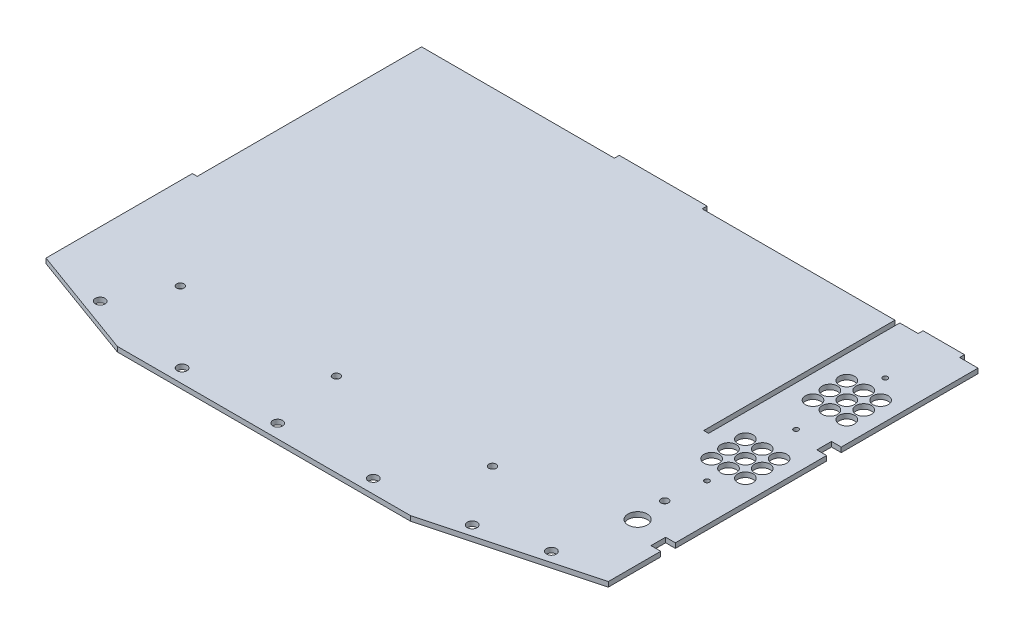
SolidWorks part; units mm, degrees
material "6061-T6 (SS)"
ref_plane "X-Y Datum" through (0, 0, 0) normal (0, 0, 1) x (1, 0, 0)
ref_plane "X-Z Datum" through (0, 0, 0) normal (0, 1, 0) x (1, 0, 0)
ref_plane "Y-Z Datum" through (0, 0, 0) normal (1, 0, 0) x (0, 0, -1)
sketch "Sketch1" plane through (0, 0, 0) normal (0, 0, 1) x (1, 0, 0)
  line L1 (-154.0408, -1.5875) -> (154.0408, -1.5875)
  line L2 (-154.0408, -1.5875) -> (-154.0408, 1.5875)
  line L3 (-154.0408, 1.5875) -> (154.0408, 1.5875)
  line L4 (154.0408, -1.5875) -> (154.0408, 1.5875)
  line L5 (-154.0408, -1.5875) -> (154.0408, 1.5875) construction
  line L6 (-154.0408, 1.5875) -> (154.0408, -1.5875) construction
  point P0 (0, 0)
  dimension "D1" = 3.175
  dimension "D2" = 308.0817
extrude "Boss-Extrude1" add sketch "Sketch1" along normal blind 267.83
sketch "Sketch3" plane through (154.0408, 0, 0) normal (1, 0, 0) x (0, 0, -1)
  line L9 (0, -1.5875) -> (0, 1.5875)
  line L10 (0, 1.5875) -> (-267.83, 1.5875)
  line L11 (-267.83, 1.5875) -> (-267.83, -1.5875)
  line L12 (-267.83, -1.5875) -> (0, -1.5875)
  line L13 (0, -1.5875) -> (0, 1.5875)
  line L14 (0, 1.5875) -> (-267.83, 1.5875)
  line L15 (-267.83, 1.5875) -> (-267.83, -1.5875)
  line L16 (-267.83, -1.5875) -> (0, -1.5875)
  dimension "D1" = 0
extrude "Boss-Extrude3" add sketch "Sketch3" along normal blind 3.175
sketch "Sketch4" plane through (0, 0, 267.83) normal (0, 0, 1) x (1, 0, 0)
  line L1 (157.2158, -1.5875) -> (208.1047, -1.5875)
  line L2 (157.2158, -1.5875) -> (157.2158, 1.5875)
  line L3 (157.2158, 1.5875) -> (208.1047, 1.5875)
  line L4 (208.1047, -1.5875) -> (208.1047, 1.5875)
  dimension "D1" = 3.175
  dimension "D2" = 50.8889
extrude "Boss-Extrude4" add sketch "Sketch4" against normal blind 267.83
sketch "Sketch6" plane through (0, 1.5875, 0) normal (0, 1, 0) x (1, 0, 0)
  line L0 (106.5047, -267.83) -> (106.5047, -223.38)
  line L1 (208.1047, -267.83) -> (-154.0408, -267.83) construction
  line L2 (208.1047, -223.38) -> (106.5047, -223.38)
  line L3 (208.1047, 0) -> (208.1047, -267.83) construction
  line L5 (106.5047, -267.83) -> (208.1047, -240.6064)
  line L7 (-154.0408, -267.83) -> (208.1047, -267.83) construction
  line L8 (208.1047, 0) -> (208.1047, -267.83) construction
  line L9 (208.1047, 0) -> (208.1047, -267.83)
  line M9 (-154.0408, -267.83) -> (208.1047, -267.83)
  line M10 (208.1047, -267.83) -> (208.1047, 0)
  dimension "D1" = 44.45
  dimension "D2" = 101.6
  dimension "D3" = 15
extrude "Cut-Extrude1" cut sketch "Sketch6" against normal through all contours L5 M9 M10
sketch "Sketch17" plane through (-154.0408, 0, 0) normal (-1, 0, 0) x (0, 0, 1)
  line L15 (267.83, -1.5875) -> (267.83, 1.5875)
  line L16 (0, -1.5875) -> (267.83, -1.5875)
  line L17 (267.83, -1.5875) -> (267.83, 1.5875)
  line L18 (267.83, 1.5875) -> (0, 1.5875)
  line L19 (0, 1.5875) -> (0, -1.5875)
  line L20 (0, -1.5875) -> (267.83, -1.5875)
  line L22 (267.83, 1.5875) -> (0, 1.5875)
  line L23 (0, 1.5875) -> (0, -1.5875)
  dimension "D1" = 0
extrude "Boss-Extrude5" add sketch "Sketch17" along normal blind 3.175
sketch "Sketch11" plane through (0, -1.5875, 0) normal (0, -1, 0) x (1, 0, 0)
  line L0 (-84.2547, 267.83) -> (-84.2547, 241.2743)
  line L1 (-157.2158, 267.83) -> (106.5047, 267.83) construction
  line L2 (-157.2158, 241.2743) -> (-84.2547, 241.2743)
  line L4 (-157.2158, 241.2743) -> (-84.2547, 267.83)
  line L6 (-157.2158, 267.83) -> (106.5047, 267.83) construction
  line L7 (-157.2158, 0) -> (-157.2158, 267.83) construction
  dimension "D2" = 26.5557
  dimension "D3" = 20
extrude "Cut-Extrude3" cut sketch "Sketch11" against normal through all
sketch "Sketch25" plane through (0, -1.5875, 0) normal (0, -1, 0) x (1, 0, 0)
  line L0 (-157.2285, 241.2697) -> (-83.9953, 267.9244) construction
  line L1 (-50.9753, 267.83) -> (-50.9753, 258.94)
  line L2 (-157.2158, 241.2743) -> (-84.2547, 267.83) construction
  line L3 (-118.0865, 255.5162) -> (-115.3222, 247.9214)
  line L5 (-84.2547, 267.83) -> (106.5047, 267.83) construction
  line L6 (-50.9753, 258.94) -> (11.2547, 258.94) construction
  line L7 (11.2547, 258.94) -> (73.4847, 258.94) construction
  line L8 (172.3981, 250.1739) -> (172.5447, 242.093)
  line L9 (106.5047, 267.83) -> (208.1047, 240.6064) construction
  line L10 (172.5447, 242.093) -> (131.9047, 252.9824) construction
  circle A0 centre (-115.3222, 247.9214) radius 3.175
  circle A1 centre (-50.9753, 258.94) radius 3.175
  circle A2 centre (11.2547, 258.94) radius 3.175
  circle A3 centre (73.4847, 258.94) radius 3.175
  circle A4 centre (172.5447, 242.093) radius 3.175
  circle A5 centre (131.9047, 252.9824) radius 3.175
  dimension "D2" = 90
  dimension "D3" = 6.35
  dimension "D13" = 8.89
  dimension "D4" = 7.7676
  dimension "D1" = 8.0823
  dimension "D5" = 33.02
  dimension "D6" = 62.23
  dimension "D7" = 62.23
  dimension "D8" = 33.02
  dimension "D9" = 35.56
  dimension "D10" = 73.96
  dimension "D11" = 40.64
  dimension "D12" = 8.0823
extrude "Cut-Extrude8" cut sketch "Sketch25" against normal blind 3.175
sketch "Sketch27" plane through (0, -1.5875, 0) normal (0, -1, 0) x (1, 0, 0)
  circle A1 centre (172.4867, 137.7748) radius 5
  circle A3 centre (183.4867, 137.7748) radius 5
  circle A11 centre (194.4867, 137.7748) radius 5
  circle A12 centre (194.4867, 126.7748) radius 5
  circle A13 centre (194.4867, 115.7748) radius 5
  circle A14 centre (183.4867, 126.7748) radius 5
  circle A15 centre (183.4867, 115.7748) radius 5
  circle A16 centre (172.4867, 115.7748) radius 5
  circle A17 centre (172.4867, 126.7748) radius 5
  circle A27 centre (194.4867, 71.7748) radius 5
  circle A28 centre (194.4867, 60.7748) radius 5
  circle A29 centre (194.4867, 49.7748) radius 5
  circle A30 centre (183.4867, 71.7748) radius 5
  circle A31 centre (183.4867, 60.7748) radius 5
  circle A32 centre (183.4867, 49.7748) radius 5
  circle A33 centre (172.4867, 49.7748) radius 5
  circle A34 centre (172.4867, 60.7748) radius 5
  circle A35 centre (172.4867, 71.7748) radius 5
extrude "Cut-Extrude9" cut sketch "Sketch27" against normal through all
sketch "Sketch31" plane through (0, -1.5875, 0) normal (0, -1, 0) x (1, 0, 0)
  circle A1 centre (183.4867, 151.7748) radius 2.4 construction
  circle A2 centre (183.4867, 151.7748) radius 1.5875
  dimension "D1" = 3.175
extrude "Cut-Extrude10" cut sketch "Sketch31" against normal through all both and the other way through all
pattern_linear "LPattern1" count 3 spacing 58 along (0, 0, -1) of "Cut-Extrude10"
sketch "Sketch34" plane through (0, -1.5875, 0) normal (0, -1, 0) x (1, 0, 0)
  point P0 (180.965, 176.776)
  point P1 (-97.7709, 213.285)
  point P2 (3.829, 213.285)
  point P3 (105.4291, 213.285)
hole_wizard "M4 Clearance Hole1" positions "Sketch34" profile "Sketch35" hole size "M4" standard "ANSI Metric" end condition through all
sketch "Sketch35" plane through (180.965, -1.5875, 176.776) normal (1, 0, 0) x (0, 0, -1)
  line L0 (0, 0) -> (0, 3.175)
  line L1 (0, 3.175) -> (2.4, 3.175)
  line L2 (2.4, 3.175) -> (2.4, 0)
  line L5 (2.4, 0) -> (0, 0)
  line L11 (0, -6.35) -> (0, 107.95) construction
  dimension "Thru Hole Dia." = 4.8
  dimension "Thru Hole Depth" = 3.175
sketch "Sketch36" plane through (0, 0, 0) normal (0, 0, -1) x (-1, 0, 0)
  line L0 (28.6512, 1.6677) -> (-28.6512, 1.6677) construction
  line L1 (0, 1.5875) -> (0, -1.5875) construction
  line L2 (-208.1047, 1.5875) -> (157.2158, 1.5875) construction
  line L3 (157.2158, -1.5875) -> (-208.1047, -1.5875) construction
  line L5 (28.575, -1.5875) -> (-28.575, -1.5875)
  line L6 (28.575, -1.5875) -> (28.575, 1.5875)
  line L7 (28.575, 1.5875) -> (-28.575, 1.5875)
  line L8 (-28.575, -1.5875) -> (-28.575, 1.5875)
  line L9 (28.575, -1.5875) -> (-28.575, 1.5875) construction
  line L10 (28.575, 1.5875) -> (-28.575, -1.5875) construction
  line L11 (-169.0911, 1.6637) -> (-196.231, 1.6637) construction
  line L12 (-182.661, 1.5875) -> (-182.661, -1.5875) construction
  line L13 (-157.216, 1.5875) -> (-195.316, 1.5875) construction
  line L14 (-169.1673, -1.5875) -> (-196.1548, -1.5875)
  line L15 (-169.1673, -1.5875) -> (-169.1673, 1.5875)
  line L16 (-169.1673, 1.5875) -> (-196.1548, 1.5875)
  line L17 (-196.1548, -1.5875) -> (-196.1548, 1.5875)
  line L18 (-169.1673, -1.5875) -> (-196.1548, 1.5875) construction
  line L19 (-169.1673, 1.5875) -> (-196.1548, -1.5875) construction
  point P0 (0, 1.6677)
  point P1 (0, 1.6677)
  point P11 (0, 0)
  point P16 (-182.661, 1.6637)
  point P21 (-182.661, 0)
  dimension "D1" = 57.15
  dimension "D2" = 26.9875
extrude "Boss-Extrude6" add sketch "Sketch36" along normal blind 3.175
sketch "Sketch37" plane through (0, -1.5875, 0) normal (0, -1, 0) x (1, 0, 0)
  line L0 (157.216, 124.442) -> (157.216, 50.8) construction
  line L1 (154.041, 124.442) -> (157.216, 124.442) construction
  line L2 (154.041, 124.442) -> (154.041, 50.8) construction
  line L3 (157.216, 124.442) -> (157.216, 0)
  line L4 (154.041, 124.442) -> (157.216, 124.442)
  line L5 (154.041, 124.442) -> (154.041, 0)
  line L6 (28.575, 0) -> (169.1673, 0) construction
  line L7 (154.041, 0) -> (157.216, 0)
  line L8 (153.9648, 124.5182) -> (157.2922, 124.5182)
  line L9 (157.2922, 124.5182) -> (157.2922, -0.0762)
  line L10 (153.9648, -0.0762) -> (157.2922, -0.0762)
  line L11 (153.9648, 124.5182) -> (153.9648, -0.0762)
  line M38 (28.575, 0) -> (169.1673, 0)
  dimension "D1" = 0.0762
extrude "Cut-Extrude11" cut sketch "Sketch37" against normal through all contours L4 L5 L3 M38
sketch "Sketch38" plane through (0, -1.5875, 0) normal (0, -1, 0) x (1, 0, 0)
  line L0 (-157.292, 146.1005) -> (-153.9646, 146.1005)
  line L1 (-157.2158, 0) -> (-154.0408, 0)
  line L2 (-157.2158, 0) -> (-157.2158, 146.0243)
  line L3 (-157.2158, 146.0243) -> (-154.0408, 146.0243)
  line L4 (-154.0408, 0) -> (-154.0408, 146.0243)
  line L5 (-153.9646, -0.0762) -> (-153.9646, 146.1005)
  line L6 (-157.292, -0.0762) -> (-153.9646, -0.0762)
  line L7 (-157.292, -0.0762) -> (-157.292, 146.1005)
  line M43 (-157.2158, 241.2743) -> (-157.2158, 0)
  line M44 (-157.2158, 0) -> (-28.575, 0)
  dimension "D1" = 3.175
  dimension "D2" = 95.25
  dimension "D3" = 0.0762
extrude "Cut-Extrude12" cut sketch "Sketch38" against normal through all contours L4 L3 M44 M43
sketch "Sketch39" plane through (0, -1.5875, 0) normal (0, -1, 0) x (1, 0, 0)
  line L0 (208.1809, 98.6135) -> (201.6785, 98.6135)
  line L1 (201.6785, 98.6135) -> (201.6785, 88.9361)
  line L2 (201.6785, 88.9361) -> (208.1809, 88.9361)
  line L3 (208.1809, 88.9361) -> (208.1809, 98.6135)
  line L4 (208.1047, 196.9623) -> (208.1047, 206.4873)
  line L5 (208.1047, 206.4873) -> (201.7547, 206.4873)
  line L6 (201.7547, 206.4873) -> (201.7547, 196.9623)
  line L7 (201.7547, 196.9623) -> (208.1047, 196.9623)
  line L8 (208.1047, 196.9623) -> (208.1047, 206.4873)
  line L9 (208.1047, 206.4873) -> (201.7547, 206.4873)
  line L10 (201.7547, 206.4873) -> (201.7547, 196.9623)
  line L11 (201.7547, 196.9623) -> (208.1047, 196.9623)
  line L12 (208.1047, 89.0123) -> (208.1047, 98.5373)
  line L13 (208.1047, 98.5373) -> (201.7547, 98.5373)
  line L14 (201.7547, 98.5373) -> (201.7547, 89.0123)
  line L15 (201.7547, 89.0123) -> (208.1047, 89.0123)
  line L16 (208.1047, 89.0123) -> (208.1047, 98.5373)
  line L17 (208.1047, 98.5373) -> (201.7547, 98.5373)
  line L18 (201.7547, 98.5373) -> (201.7547, 89.0123)
  line L19 (201.7547, 89.0123) -> (208.1047, 89.0123)
  line L20 (208.1809, 206.5635) -> (201.6785, 206.5635)
  line L21 (201.6785, 206.5635) -> (201.6785, 196.8861)
  line L22 (201.6785, 196.8861) -> (208.1809, 196.8861)
  line L23 (208.1809, 196.8861) -> (208.1809, 206.5635)
  dimension "D1" = 0
  dimension "D2" = 0
  dimension "D3" = 0.0762
extrude "Cut-Extrude13" cut sketch "Sketch39" against normal through all contours L18 L19 L16 L17 | L10 L11 L8 L9
sketch "Sketch40" plane through (0, -1.5875, 0) normal (0, -1, 0) x (1, 0, 0)
  circle A0 centre (182.661, 196.101) radius 6.25
  point P0 (182.661, 196.101)
  dimension "D1" = 12.5
extrude "Cut-Extrude14" cut sketch "Sketch40" against normal through all
